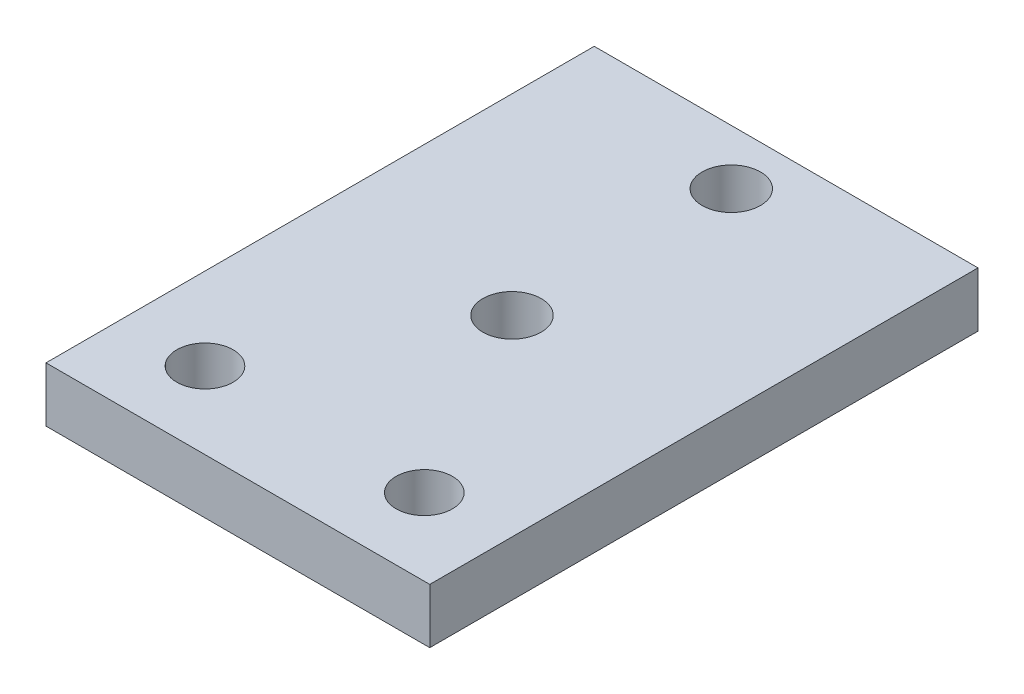
SolidWorks part; units mm, degrees
ref_plane "Front Plane" through (0, 0, 0) normal (0, 0, 1) x (1, 0, 0)
ref_plane "Top Plane" through (0, 0, 0) normal (0, 1, 0) x (1, 0, 0)
ref_plane "Right Plane" through (0, 0, 0) normal (1, 0, 0) x (0, 0, -1)
sketch "Sketch1" plane through (0, 0, 0) normal (0, 1, 0) x (1, 0, 0)
  line L1 (-22.225, -31.75) -> (22.225, -31.75)
  line L2 (-22.225, -31.75) -> (-22.225, 31.75)
  line L3 (-22.225, 31.75) -> (22.225, 31.75)
  line L4 (22.225, -31.75) -> (22.225, 31.75)
  line L5 (-22.225, -31.75) -> (22.225, 31.75) construction
  line L6 (-22.225, 31.75) -> (22.225, -31.75) construction
  point P0 (0, 0)
  dimension "D1" = 44.45
  dimension "D2" = 63.5
extrude "Boss-Extrude1" add sketch "Sketch1" along normal blind 6.35
sketch "Sketch2" plane through (0, 6.35, 0) normal (0, 1, 0) x (1, 0, 0)
  line L0 (0, -3.4925) -> (0, 3.4925) construction
  line L1 (22.225, 31.75) -> (-22.225, 31.75) construction
  line L2 (-12.7, -22.86) -> (12.7, -22.86) construction
  line L3 (-22.225, -31.75) -> (22.225, -31.75) construction
  point P0 (0, 25.4)
  point P1 (0, 0)
  point P6 (-12.7, -22.86)
  point P7 (12.7, -22.86)
  point P10 (0, -22.86)
  point P13 (0, 0)
  dimension "D1" = 6.35
  dimension "D2" = 25.4
  dimension "D3" = 8.89
  dimension "D4" = 25.4
hole_wizard "1/4 Clearance Hole1" positions "Sketch5" profile "Sketch6" hole size "1/4" standard "ANSI Inch" end condition through all
sketch "Sketch5" plane through (0, 6.35, 0) normal (0, 1, 0) x (1, 0, 0)
  point P3 (0, 25.4)
  point P9 (0, 0)
  dimension "D1" = 25.4
sketch "Sketch6" plane through (0, 6.35, -25.4) normal (1, 0, 0) x (0, 0, 1)
  line L0 (0, 0) -> (0, 6.35)
  line L1 (0, 6.35) -> (3.3782, 6.35)
  line L2 (3.3782, 6.35) -> (3.3782, 0)
  line L5 (3.3782, 0) -> (0, 0)
  line L11 (0, -6.35) -> (0, 107.95) construction
  dimension "Thru Hole Dia." = 6.7564
  dimension "Thru Hole Depth" = 6.35
hole_wizard "1/4 Clearance Hole3" positions "Sketch7" profile "Sketch8" hole size "1/4" standard "ANSI Inch" end condition through all
sketch "Sketch7" plane through (0, 6.35, 0) normal (0, 1, 0) x (1, 0, 0)
  point P0 (-12.7, -22.86)
  point P3 (12.7, -22.86)
sketch "Sketch8" plane through (-12.7, 6.35, 22.86) normal (1, 0, 0) x (0, 0, 1)
  line L0 (0, 0) -> (0, 6.35)
  line L1 (0, 6.35) -> (3.2639, 6.35)
  line L2 (3.2639, 6.35) -> (3.2639, 0)
  line L5 (3.2639, 0) -> (0, 0)
  line L11 (0, -6.35) -> (0, 107.95) construction
  dimension "Thru Hole Dia." = 6.5278
  dimension "Thru Hole Depth" = 6.35
